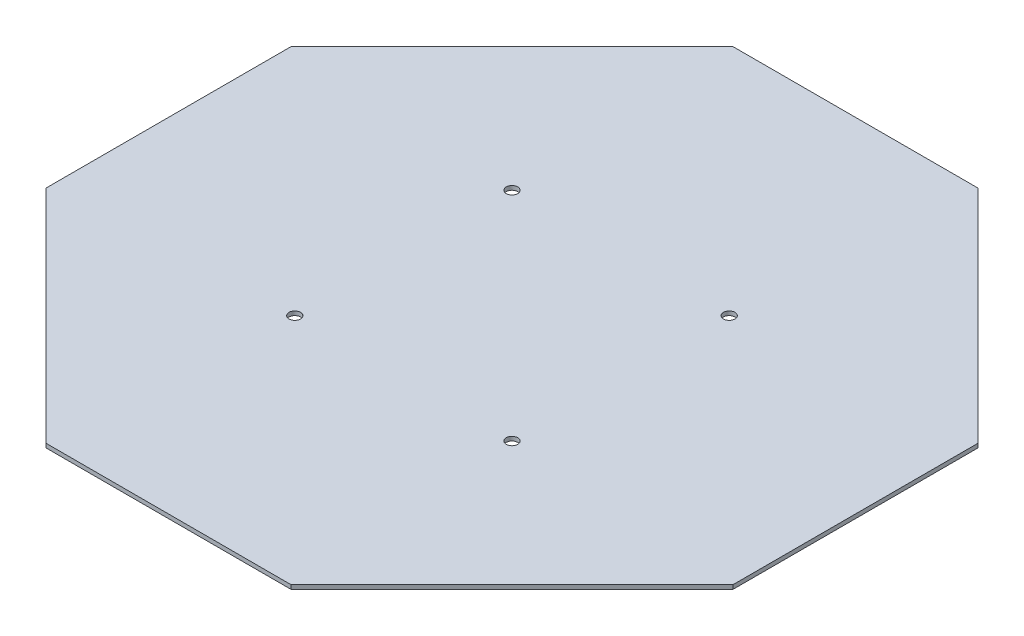
SolidWorks part; units mm, degrees
ref_plane "Front Plane" through (0, 0, 0) normal (0, 0, 1) x (1, 0, 0)
ref_plane "Top Plane" through (0, 0, 0) normal (0, 1, 0) x (1, 0, 0)
ref_plane "Right Plane" through (0, 0, 0) normal (1, 0, 0) x (0, 0, -1)
sketch "Sketch1" plane through (0, 0, 0) normal (0, 1, 0) x (1, 0, 0)
  line L0 (-89, 250) -> (89, 250) construction
  line L1 (89, 250) -> (250, 89) construction
  line L2 (250, 89) -> (250, -89) construction
  line L3 (250, -89) -> (89, -250) construction
  line L4 (89, -250) -> (-89, -250) construction
  line L5 (-89, -250) -> (-250, -89) construction
  line L6 (-250, -89) -> (-250, 89) construction
  line L7 (-250, 89) -> (-89, 250) construction
  line L8 (0, 250) -> (0, -250) construction
  line L9 (-250, 0) -> (250, 0) construction
  line L10 (-253, 90.2426) -> (-90.2426, 253)
  line L11 (-90.2426, 253) -> (90.2426, 253)
  line L12 (90.2426, 253) -> (253, 90.2426)
  line L13 (253, 90.2426) -> (253, -90.2426)
  line L14 (253, -90.2426) -> (90.2426, -253)
  line L15 (90.2426, -253) -> (-90.2426, -253)
  line L16 (-90.2426, -253) -> (-253, -90.2426)
  line L17 (-253, -90.2426) -> (-253, 90.2426)
  point P13 (-250, -89.2371)
  dimension "D1" = 500
  dimension "D2" = 178
  dimension "D3" = 3
extrude "Boss-Extrude1" add sketch "Sketch1" along normal blind 3
sketch "Sketch2" plane through (0, 3, 0) normal (0, 1, 0) x (1, 0, 0)
  line L1 (-80, -80) -> (80, -80) construction
  line L2 (-80, -80) -> (-80, 80) construction
  line L3 (-80, 80) -> (80, 80) construction
  line L4 (80, -80) -> (80, 80) construction
  line L5 (-80, -80) -> (80, 80) construction
  line L6 (-80, 80) -> (80, -80) construction
  circle A0 centre (-80, 80) radius 4.25
  circle A1 centre (80, 80) radius 4.25
  circle A2 centre (80, -80) radius 4.25
  circle A3 centre (-80, -80) radius 4.25
  point P0 (0, 0)
  dimension "D2" = 8.5
  dimension "D1" = 160
extrude "Cut-Extrude1" cut sketch "Sketch2" against normal through all both
